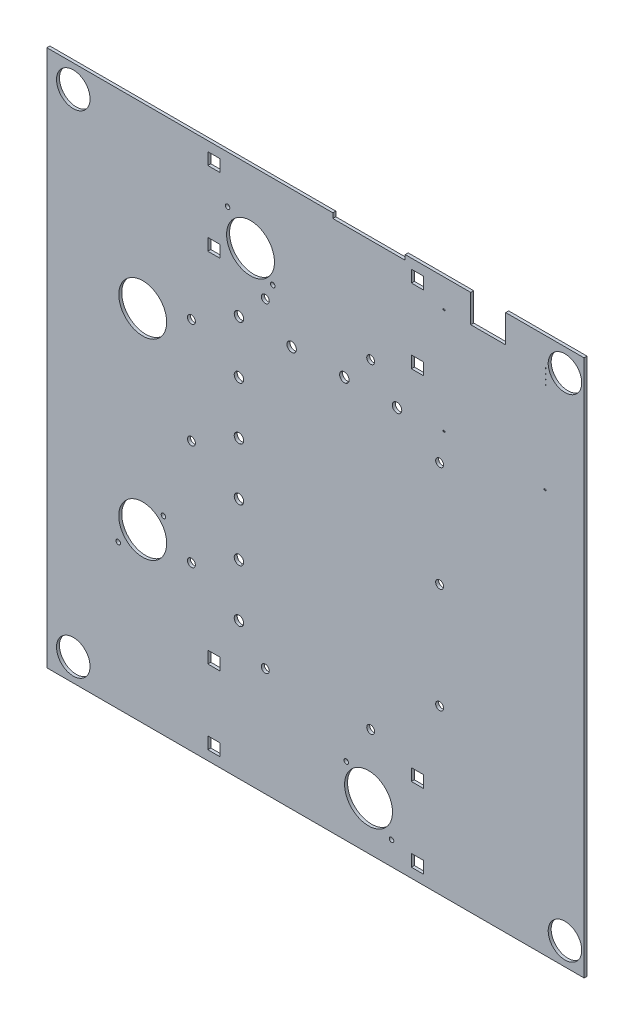
SolidWorks part; units mm, degrees
ref_plane "Front Plane" through (0, 0, 0) normal (0, 0, 1) x (1, 0, 0)
ref_plane "Top Plane" through (0, 0, 0) normal (0, 1, 0) x (1, 0, 0)
ref_plane "Right Plane" through (0, 0, 0) normal (1, 0, 0) x (0, 0, -1)
sketch "Sketch3" plane through (0, 0, 0) normal (0, 0, 1) x (1, 0, 0)
  line L0 (-165.3493, -19.4174) -> (-165.3493, -25.7674) construction
  line L1 (-165.3493, -19.4174) -> (-158.9993, -19.4174) construction
  line L2 (-216.1967, -299.1275) -> (-216.1967, -226.5584) construction
  line L3 (-133.8855, -14.3374) -> (-115.3437, -14.3374)
  line L4 (-133.8855, -14.3374) -> (-133.8855, -29.1775)
  line L5 (-133.8855, -29.1775) -> (-115.3437, -29.1775)
  line L6 (-115.3437, -14.3374) -> (-115.3437, -29.1775)
  line L7 (-168.6239, -14.3374) -> (-206.9898, -14.3374)
  line L8 (-73.7823, -14.3374) -> (-358.611, -14.3374)
  line L9 (-358.611, -14.3374) -> (-358.611, -299.1275)
  line L10 (-358.611, -299.1275) -> (-73.7823, -299.1275)
  line L11 (-73.7823, -299.1275) -> (-73.7823, -14.3374)
  line L14 (-168.6239, -14.3374) -> (-168.6239, -16.9636)
  line L15 (-168.6239, -16.9636) -> (-206.9898, -16.9636)
  line L18 (-151.6188, -156.7325) -> (-151.6188, -154.9678)
  line L19 (-216.1967, -86.8605) -> (-216.1967, -14.3374) construction
  line L20 (-158.9993, -19.4174) -> (-158.9993, -25.7674) construction
  line L21 (-165.3493, -25.7674) -> (-158.9993, -25.7674) construction
  line L22 (-165.3493, -19.4174) -> (-165.3493, -25.7674)
  line L23 (-165.3493, -19.4174) -> (-158.9993, -19.4174)
  line L24 (-158.9993, -19.4174) -> (-158.9993, -25.7674)
  line L25 (-165.3493, -25.7674) -> (-158.9993, -25.7674)
  line L27 (-165.3493, -294.0475) -> (-165.3493, -287.6975) construction
  line L28 (-165.3493, -287.6975) -> (-158.9993, -287.6975) construction
  line L29 (-158.9993, -287.6975) -> (-158.9993, -294.0475) construction
  line L30 (-158.9993, -294.0475) -> (-165.3493, -294.0475) construction
  line L31 (-158.9993, -65.1374) -> (-158.9993, -58.7874)
  line L32 (-165.3493, -65.1374) -> (-158.9993, -65.1374)
  line L33 (-165.3493, -58.7874) -> (-165.3493, -65.1374)
  line L34 (-158.9993, -58.7874) -> (-165.3493, -58.7874)
  line L35 (-158.9993, -65.1374) -> (-158.9993, -58.7874)
  line L36 (-165.3493, -65.1374) -> (-158.9993, -65.1374)
  line L37 (-165.3493, -58.7874) -> (-165.3493, -65.1374)
  line L38 (-158.9993, -58.7874) -> (-165.3493, -58.7874)
  line L39 (-266.9493, -65.1374) -> (-266.9493, -58.7874)
  line L40 (-273.2993, -65.1374) -> (-266.9493, -65.1374)
  line L41 (-273.2993, -58.7874) -> (-273.2993, -65.1374)
  line L42 (-266.9493, -58.7874) -> (-273.2993, -58.7874)
  line L43 (-266.9493, -65.1374) -> (-266.9493, -58.7874)
  line L44 (-273.2993, -65.1374) -> (-266.9493, -65.1374)
  line L45 (-273.2993, -58.7874) -> (-273.2993, -65.1374)
  line L46 (-266.9493, -58.7874) -> (-273.2993, -58.7874)
  line L47 (-266.9493, -25.7674) -> (-266.9493, -19.4174)
  line L48 (-273.2993, -25.7674) -> (-266.9493, -25.7674)
  line L49 (-273.2993, -19.4174) -> (-273.2993, -25.7674)
  line L50 (-266.9493, -19.4174) -> (-273.2993, -19.4174)
  line L51 (-266.9493, -25.7674) -> (-266.9493, -19.4174)
  line L52 (-273.2993, -25.7674) -> (-266.9493, -25.7674)
  line L53 (-273.2993, -19.4174) -> (-273.2993, -25.7674)
  line L54 (-266.9493, -19.4174) -> (-273.2993, -19.4174)
  line L55 (-165.3493, -254.6775) -> (-165.3493, -248.3275) construction
  line L56 (-165.3493, -248.3275) -> (-158.9993, -248.3275) construction
  line L57 (-158.9993, -248.3275) -> (-158.9993, -254.6775) construction
  line L58 (-158.9993, -254.6775) -> (-165.3493, -254.6775) construction
  line L59 (-273.2993, -294.0475) -> (-273.2993, -287.6975) construction
  line L60 (-273.2993, -287.6975) -> (-266.9493, -287.6975) construction
  line L61 (-266.9493, -287.6975) -> (-266.9493, -294.0475) construction
  line L62 (-266.9493, -294.0475) -> (-273.2993, -294.0475) construction
  line L63 (-273.2993, -254.6775) -> (-273.2993, -248.3275) construction
  line L64 (-273.2993, -248.3275) -> (-266.9493, -248.3275) construction
  line L65 (-266.9493, -248.3275) -> (-266.9493, -254.6775) construction
  line L66 (-266.9493, -254.6775) -> (-273.2993, -254.6775) construction
  line L67 (-165.3493, -294.0475) -> (-165.3493, -287.6975)
  line L68 (-165.3493, -287.6975) -> (-158.9993, -287.6975)
  line L69 (-158.9993, -287.6975) -> (-158.9993, -294.0475)
  line L70 (-158.9993, -294.0475) -> (-165.3493, -294.0475)
  line L71 (-165.3493, -254.6775) -> (-165.3493, -248.3275)
  line L72 (-165.3493, -248.3275) -> (-158.9993, -248.3275)
  line L73 (-158.9993, -248.3275) -> (-158.9993, -254.6775)
  line L74 (-158.9993, -254.6775) -> (-165.3493, -254.6775)
  line L75 (-273.2993, -294.0475) -> (-273.2993, -287.6975)
  line L76 (-273.2993, -287.6975) -> (-266.9493, -287.6975)
  line L77 (-266.9493, -287.6975) -> (-266.9493, -294.0475)
  line L78 (-266.9493, -294.0475) -> (-273.2993, -294.0475)
  line L79 (-273.2993, -254.6775) -> (-273.2993, -248.3275)
  line L80 (-273.2993, -248.3275) -> (-266.9493, -248.3275)
  line L81 (-266.9493, -248.3275) -> (-266.9493, -254.6775)
  line L82 (-266.9493, -254.6775) -> (-273.2993, -254.6775)
  line L120 (-116.6137, -27.9075) -> (-132.6155, -27.9075)
  line L121 (-132.6155, -27.9075) -> (-132.6155, -6.6988)
  line L122 (-132.6155, -6.6988) -> (-116.6137, -6.6988)
  line L123 (-116.6137, -6.6988) -> (-116.6137, -27.9075)
  line L124 (-205.7198, -6.6988) -> (-205.7198, -24.3985)
  line L125 (-205.7198, -24.3985) -> (-190.42, -24.3985)
  line L126 (-190.42, -24.3985) -> (-190.42, -6.6988)
  line L127 (-190.42, -6.6988) -> (-205.7198, -6.6988)
  line L128 (-185.1936, -6.6988) -> (-185.1936, -24.3985)
  line L129 (-185.1936, -24.3985) -> (-169.8939, -24.3985)
  line L130 (-169.8939, -24.3985) -> (-169.8939, -6.6988)
  line L131 (-169.8939, -6.6988) -> (-185.1936, -6.6988)
  line L132 (-147.4742, -29.0504) -> (-148.6172, -29.0504)
  line L133 (-148.6172, -29.0504) -> (-148.6172, -29.6854)
  line L134 (-148.6172, -29.6854) -> (-147.4742, -29.6854)
  line L135 (-147.4742, -29.6854) -> (-147.4742, -29.0504)
  line L136 (-147.4742, -84.9296) -> (-148.6172, -84.9296)
  line L137 (-148.6172, -84.9296) -> (-148.6172, -85.5646)
  line L138 (-148.6172, -85.5646) -> (-147.4742, -85.5646)
  line L139 (-147.4742, -85.5646) -> (-147.4742, -84.9296)
  line L140 (-95.024, -85.5646) -> (-93.881, -85.5646)
  line L141 (-93.881, -85.5646) -> (-93.881, -84.9296)
  line L142 (-93.881, -84.9296) -> (-95.024, -84.9296)
  line L143 (-95.024, -84.9296) -> (-95.024, -85.5646)
  line L144 (-95.024, -37.3053) -> (-93.881, -37.3053)
  line L145 (-93.881, -37.3053) -> (-93.881, -36.6703)
  line L146 (-93.881, -36.6703) -> (-95.024, -36.6703)
  line L147 (-95.024, -36.6703) -> (-95.024, -37.3053)
  line L148 (-95.024, -34.7654) -> (-93.881, -34.7654)
  line L149 (-93.881, -34.7654) -> (-93.881, -34.1304)
  line L150 (-93.881, -34.1304) -> (-95.024, -34.1304)
  line L151 (-95.024, -34.1304) -> (-95.024, -34.7654)
  line L152 (-95.024, -32.2254) -> (-93.881, -32.2254)
  line L153 (-93.881, -32.2254) -> (-93.881, -31.5904)
  line L154 (-93.881, -31.5904) -> (-95.024, -31.5904)
  line L155 (-95.024, -31.5904) -> (-95.024, -32.2254)
  line L156 (-95.024, -29.6854) -> (-93.881, -29.6854)
  line L157 (-93.881, -29.6854) -> (-93.881, -29.0504)
  line L158 (-93.881, -29.0504) -> (-95.024, -29.0504)
  line L159 (-95.024, -29.0504) -> (-95.024, -29.6854)
  line L160 (-94.135, -82.8976) -> (-94.135, -15.5887)
  line L161 (-100.4849, -9.2387) -> (-142.3943, -9.2387)
  line L162 (-148.7442, -15.5887) -> (-148.7442, -82.8976)
  line L163 (-136.0444, -95.5974) -> (-106.8348, -95.5974)
  line L184 (-215.778, -86.8605) -> (-216.1967, -86.8605)
  line L186 (-216.1967, -226.5584) -> (-215.778, -226.5584)
  line L224 (-204.4327, -15.6936) -> (-202.6623, -15.6936)
  line L225 (-204.1848, -12.9437) -> (-204.4327, -12.9437)
  line L226 (-202.6623, -12.9437) -> (-203.3848, -12.9437)
  line L227 (-191.7071, -12.9437) -> (-193.4774, -12.9437)
  line L228 (-191.955, -15.6936) -> (-191.7071, -15.6936)
  line L229 (-193.4774, -15.6936) -> (-192.755, -15.6936)
  line L230 (-171.181, -12.9437) -> (-172.9513, -12.9437)
  line L231 (-171.4288, -15.6936) -> (-171.181, -15.6936)
  line L232 (-172.9513, -15.6936) -> (-172.2288, -15.6936)
  line L233 (-183.9066, -15.6936) -> (-182.1362, -15.6936)
  line L234 (-183.6587, -12.9437) -> (-183.9066, -12.9437)
  line L235 (-182.1362, -12.9437) -> (-182.8587, -12.9437)
  line L236 (-206.9898, -14.3374) -> (-206.9898, -16.9636)
  line L237 (-358.611, -156.7325) -> (-73.7823, -156.7325) construction
  circle A3 centre (-250.661, -52.4374) radius 12.7
  circle A4 centre (-188.0823, -273.7275) radius 12.7
  circle A10 centre (-83.9173, -26.4411) radius 8.8899
  circle A11 centre (-344.6391, -26.4411) radius 8.8899
  circle A12 centre (-307.811, -210.2275) radius 12.7
  circle A13 centre (-307.811, -108.6275) radius 12.7
  arc A15 (-296.0366, -23.5764) -> (-295.6619, -23.6712) centre (-295.7929, -23.4014) ccw
  arc A20 (-294.3481, -26.589) -> (-294.5085, -26.9278) centre (-294.2166, -26.8586) ccw
  circle A21 centre (-242.8212, -71.7774) radius 2.1 construction
  circle A22 centre (-242.8212, -71.7774) radius 2.1
  circle A23 centre (-186.9412, -71.7774) radius 2.1 construction
  circle A24 centre (-186.9412, -71.7774) radius 2.1
  circle A25 centre (-150.3993, -100.7974) radius 2.1 construction
  circle A26 centre (-150.3993, -100.7974) radius 2.1
  circle A27 centre (-150.3993, -156.6774) radius 2.1 construction
  arc A29 (-332.9771, -238.3425) -> (-332.6024, -238.4374) centre (-332.7334, -238.1675) ccw
  arc A34 (-331.2886, -241.3551) -> (-331.449, -241.6939) centre (-331.1571, -241.6247) ccw
  circle A35 centre (-150.3993, -156.6774) radius 2.1
  circle A36 centre (-150.3993, -212.5574) radius 2.1 construction
  circle A37 centre (-150.3993, -212.5574) radius 2.1
  circle A38 centre (-186.9412, -241.5774) radius 2.1 construction
  circle A39 centre (-186.9412, -241.5774) radius 2.1
  circle A40 centre (-242.8212, -241.5774) radius 2.1 construction
  circle A41 centre (-242.8212, -241.5774) radius 2.1
  circle A42 centre (-282.0012, -212.5574) radius 2.1 construction
  circle A43 centre (-282.0012, -212.5574) radius 2.1
  circle A44 centre (-282.0012, -156.6774) radius 2.1 construction
  circle A45 centre (-282.0012, -156.6774) radius 2.1
  circle A46 centre (-282.0012, -100.7974) radius 2.1 construction
  circle A47 centre (-282.0012, -100.7974) radius 2.1
  circle A48 centre (-320.8045, -222.4214) radius 1.1994 construction
  circle A49 centre (-320.8045, -222.4214) radius 1.1994
  circle A50 centre (-296.8165, -198.4311) radius 1.1994 construction
  circle A51 centre (-296.8165, -198.4311) radius 1.1994
  circle A52 centre (-175.8884, -286.721) radius 1.1994 construction
  circle A53 centre (-175.8884, -286.721) radius 1.1994
  arc A54 (-296.0366, -23.5764) -> (-295.6619, -23.6712) centre (-295.7929, -23.4014) ccw
  circle A55 centre (-199.8787, -262.733) radius 1.1994 construction
  circle A56 centre (-199.8787, -262.733) radius 1.1994
  circle A57 centre (-262.8549, -39.4439) radius 1.1994 construction
  circle A58 centre (-262.8549, -39.4439) radius 1.1994
  arc A59 (-294.3481, -26.589) -> (-294.5085, -26.9278) centre (-294.2166, -26.8586) ccw
  circle A60 centre (-238.8646, -63.4319) radius 1.1994 construction
  arc A61 (-332.9771, -238.3425) -> (-332.6024, -238.4374) centre (-332.7334, -238.1675) ccw
  circle A62 centre (-238.8646, -63.4319) radius 1.1994
  arc A66 (-331.2886, -241.3551) -> (-331.449, -241.6939) centre (-331.1571, -241.6247) ccw
  arc A68 (-81.1216, -256.7776) -> (-81.2164, -257.1523) centre (-80.9465, -257.0213) ccw
  arc A73 (-84.1341, -258.4661) -> (-84.4729, -258.3057) centre (-84.4038, -258.5976) ccw
  arc A74 (-106.8348, -95.5974) -> (-94.135, -82.8976) centre (-106.8348, -82.8976) ccw
  arc A75 (-94.135, -15.5887) -> (-100.4849, -9.2387) centre (-100.4849, -15.5887) ccw
  arc A76 (-142.3943, -9.2387) -> (-148.7442, -15.5887) centre (-142.3943, -15.5887) ccw
  arc A77 (-148.7442, -82.8976) -> (-136.0444, -95.5974) centre (-136.0444, -82.8976) ccw
  circle A79 centre (-344.6391, -287.0239) radius 8.8899
  circle A105 centre (-83.9173, -287.0239) radius 8.8899
  arc A124 (-203.3848, -13.0248) -> (-204.1848, -13.0248) centre (-203.7848, -14.3187) ccw
  arc A125 (-202.6623, -15.6936) -> (-202.6623, -12.9437) centre (-203.7848, -14.3187) ccw
  arc A126 (-204.4327, -12.9437) -> (-204.4327, -15.6936) centre (-203.7848, -14.3187) ccw
  arc A127 (-193.4774, -12.9437) -> (-193.4774, -15.6936) centre (-192.355, -14.3187) ccw
  arc A128 (-191.7071, -15.6936) -> (-191.7071, -12.9437) centre (-192.355, -14.3187) ccw
  arc A129 (-192.755, -15.6126) -> (-191.955, -15.6126) centre (-192.355, -14.3187) ccw
  arc A130 (-172.9513, -12.9437) -> (-172.9513, -15.6936) centre (-171.8288, -14.3187) ccw
  arc A131 (-171.181, -15.6936) -> (-171.181, -12.9437) centre (-171.8288, -14.3187) ccw
  arc A132 (-182.1362, -15.6936) -> (-182.1362, -12.9437) centre (-183.2587, -14.3187) ccw
  arc A133 (-183.9066, -12.9437) -> (-183.9066, -15.6936) centre (-183.2587, -14.3187) ccw
  arc A134 (-182.8587, -13.0248) -> (-183.6587, -13.0248) centre (-183.2587, -14.3187) ccw
  circle A135 centre (-181.9887, -23.2085) radius 0.23
  circle A136 centre (-180.7187, -20.6686) radius 0.23
  circle A137 centre (-178.1787, -20.6686) radius 0.23
  circle A138 centre (-175.6388, -20.6686) radius 0.23
  circle A139 centre (-176.9088, -23.2085) radius 0.23
  circle A140 centre (-174.3688, -23.2085) radius 0.23
  circle A141 centre (-173.0988, -20.6686) radius 0.23
  spline S0 degree 3 poles (-173.0628, -89.332) (-172.7853, -89.3367) (-172.38, -89.2807) (-171.8457, -89.0944) (-171.369, -88.7792) (-170.9954, -88.3966) (-170.7252, -87.9738) (-170.5413, -87.5071) (-170.4563, -87.0124) (-170.468, -86.5105) (-170.5819, -86.0212) (-170.7877, -85.5631) (-171.0825, -85.1566) (-171.4498, -84.8146) (-171.879, -84.5546) (-172.3499, -84.382) (-172.847, -84.3088) (-173.3494, -84.3327) (-173.8366, -84.4589) (-174.2897, -84.6762) (-174.6885, -84.981) (-175.0212, -85.3565) (-175.2704, -85.7919) (-175.4312, -86.2669) (-175.492, -86.7649) (-175.456, -87.2652) (-175.3187, -87.7482) (-175.0911, -88.1957) (-174.7769, -88.5877) (-174.3932, -88.9116) (-173.9523, -89.1509) (-173.5614, -89.2712) (-173.2532, -89.3211) (-173.0628, -89.332) (-172.7853, -89.3367) (-172.38, -89.2807) knots -0.036354 -0.02215 -0.008468 0 0.030815 0.06902 0.107055 0.13877 0.170453 0.202182 0.233878 0.265639 0.297366 0.329129 0.360857 0.392587 0.424284 0.456 0.487682 0.519541 0.551366 0.583108 0.614815 0.646536 0.67822 0.709939 0.741619 0.773352 0.805047 0.836812 0.868541 0.900301 0.932026 0.963646 0.97785 0.991532 1 1.030815 1.06902 1.107055 only from (-172.9024, -89.3332) to (-172.9024, -89.3332) construction
  spline S1 degree 3 poles (-173.0628, -89.332) (-172.7853, -89.3367) (-172.38, -89.2807) (-171.8457, -89.0944) (-171.369, -88.7792) (-170.9954, -88.3966) (-170.7252, -87.9738) (-170.5413, -87.5071) (-170.4563, -87.0124) (-170.468, -86.5105) (-170.5819, -86.0212) (-170.7877, -85.5631) (-171.0825, -85.1566) (-171.4498, -84.8146) (-171.879, -84.5546) (-172.3499, -84.382) (-172.847, -84.3088) (-173.3494, -84.3327) (-173.8366, -84.4589) (-174.2897, -84.6762) (-174.6885, -84.981) (-175.0212, -85.3565) (-175.2704, -85.7919) (-175.4312, -86.2669) (-175.492, -86.7649) (-175.456, -87.2652) (-175.3187, -87.7482) (-175.0911, -88.1957) (-174.7769, -88.5877) (-174.3932, -88.9116) (-173.9523, -89.1509) (-173.5614, -89.2712) (-173.2532, -89.3211) (-173.0628, -89.332) (-172.7853, -89.3367) (-172.38, -89.2807) knots -0.036354 -0.02215 -0.008468 0 0.030815 0.06902 0.107055 0.13877 0.170453 0.202182 0.233878 0.265639 0.297366 0.329129 0.360857 0.392587 0.424284 0.456 0.487682 0.519541 0.551366 0.583108 0.614815 0.646536 0.67822 0.709939 0.741619 0.773352 0.805047 0.836812 0.868541 0.900301 0.932026 0.963646 0.97785 0.991532 1 1.030815 1.06902 1.107055 only from (-172.9024, -89.3332) to (-172.9024, -89.3332)
  spline S2 degree 3 poles (-200.8196, -84.3229) (-201.0971, -84.3182) (-201.5024, -84.3742) (-202.0367, -84.5605) (-202.5133, -84.8757) (-202.8869, -85.2583) (-203.1572, -85.681) (-203.341, -86.1477) (-203.4261, -86.6425) (-203.4143, -87.1444) (-203.3005, -87.6337) (-203.0947, -88.0918) (-202.7998, -88.4983) (-202.4325, -88.8403) (-202.0033, -89.1003) (-201.5324, -89.2729) (-201.0354, -89.3461) (-200.533, -89.3222) (-200.0457, -89.196) (-199.5927, -88.9787) (-199.1938, -88.6739) (-198.8612, -88.2984) (-198.612, -87.863) (-198.4511, -87.388) (-198.3903, -86.89) (-198.4263, -86.3896) (-198.5636, -85.9067) (-198.7912, -85.4592) (-199.1055, -85.0672) (-199.4891, -84.7433) (-199.9301, -84.504) (-200.321, -84.3837) (-200.6292, -84.3338) (-200.8196, -84.3229) (-201.0971, -84.3182) (-201.5024, -84.3742) knots -0.036354 -0.02215 -0.008468 0 0.030815 0.06902 0.107055 0.13877 0.170453 0.202182 0.233878 0.265639 0.297366 0.329129 0.360857 0.392587 0.424284 0.456 0.487682 0.519541 0.551366 0.583108 0.614815 0.646536 0.67822 0.709939 0.741619 0.773352 0.805047 0.836812 0.868541 0.900301 0.932026 0.963646 0.97785 0.991532 1 1.030815 1.06902 1.107055 only from (-200.98, -84.3216) to (-200.98, -84.3216) construction
  spline S3 degree 3 poles (-200.8196, -84.3229) (-201.0971, -84.3182) (-201.5024, -84.3742) (-202.0367, -84.5605) (-202.5133, -84.8757) (-202.8869, -85.2583) (-203.1572, -85.681) (-203.341, -86.1477) (-203.4261, -86.6425) (-203.4143, -87.1444) (-203.3005, -87.6337) (-203.0947, -88.0918) (-202.7998, -88.4983) (-202.4325, -88.8403) (-202.0033, -89.1003) (-201.5324, -89.2729) (-201.0354, -89.3461) (-200.533, -89.3222) (-200.0457, -89.196) (-199.5927, -88.9787) (-199.1938, -88.6739) (-198.8612, -88.2984) (-198.612, -87.863) (-198.4511, -87.388) (-198.3903, -86.89) (-198.4263, -86.3896) (-198.5636, -85.9067) (-198.7912, -85.4592) (-199.1055, -85.0672) (-199.4891, -84.7433) (-199.9301, -84.504) (-200.321, -84.3837) (-200.6292, -84.3338) (-200.8196, -84.3229) (-201.0971, -84.3182) (-201.5024, -84.3742) knots -0.036354 -0.02215 -0.008468 0 0.030815 0.06902 0.107055 0.13877 0.170453 0.202182 0.233878 0.265639 0.297366 0.329129 0.360857 0.392587 0.424284 0.456 0.487682 0.519541 0.551366 0.583108 0.614815 0.646536 0.67822 0.709939 0.741619 0.773352 0.805047 0.836812 0.868541 0.900301 0.932026 0.963646 0.97785 0.991532 1 1.030815 1.06902 1.107055 only from (-200.98, -84.3216) to (-200.98, -84.3216)
  spline S4 degree 3 poles (-256.6996, -224.0229) (-256.9771, -224.0182) (-257.3824, -224.0742) (-257.9167, -224.2605) (-258.3933, -224.5757) (-258.7669, -224.9583) (-259.0372, -225.381) (-259.221, -225.8477) (-259.3061, -226.3425) (-259.2943, -226.8444) (-259.1805, -227.3337) (-258.9747, -227.7918) (-258.6798, -228.1983) (-258.3125, -228.5403) (-257.8833, -228.8003) (-257.4124, -228.9729) (-256.9154, -229.0461) (-256.413, -229.0222) (-255.9257, -228.896) (-255.4727, -228.6787) (-255.0738, -228.3739) (-254.7412, -227.9984) (-254.492, -227.563) (-254.3311, -227.088) (-254.2703, -226.59) (-254.3063, -226.0896) (-254.4436, -225.6067) (-254.6712, -225.1592) (-254.9855, -224.7672) (-255.3691, -224.4433) (-255.8101, -224.204) (-256.201, -224.0837) (-256.5092, -224.0338) (-256.6996, -224.0229) (-256.9771, -224.0182) (-257.3824, -224.0742) knots -0.036354 -0.02215 -0.008468 0 0.030815 0.06902 0.107055 0.13877 0.170453 0.202182 0.233878 0.265639 0.297366 0.329129 0.360857 0.392587 0.424284 0.456 0.487682 0.519541 0.551366 0.583108 0.614815 0.646536 0.67822 0.709939 0.741619 0.773352 0.805047 0.836812 0.868541 0.900301 0.932026 0.963646 0.97785 0.991532 1 1.030815 1.06902 1.107055 only from (-256.86, -224.0216) to (-256.86, -224.0216) construction
  spline S5 degree 3 poles (-256.6996, -224.0229) (-256.9771, -224.0182) (-257.3824, -224.0742) (-257.9167, -224.2605) (-258.3933, -224.5757) (-258.7669, -224.9583) (-259.0372, -225.381) (-259.221, -225.8477) (-259.3061, -226.3425) (-259.2943, -226.8444) (-259.1805, -227.3337) (-258.9747, -227.7918) (-258.6798, -228.1983) (-258.3125, -228.5403) (-257.8833, -228.8003) (-257.4124, -228.9729) (-256.9154, -229.0461) (-256.413, -229.0222) (-255.9257, -228.896) (-255.4727, -228.6787) (-255.0738, -228.3739) (-254.7412, -227.9984) (-254.492, -227.563) (-254.3311, -227.088) (-254.2703, -226.59) (-254.3063, -226.0896) (-254.4436, -225.6067) (-254.6712, -225.1592) (-254.9855, -224.7672) (-255.3691, -224.4433) (-255.8101, -224.204) (-256.201, -224.0837) (-256.5092, -224.0338) (-256.6996, -224.0229) (-256.9771, -224.0182) (-257.3824, -224.0742) knots -0.036354 -0.02215 -0.008468 0 0.030815 0.06902 0.107055 0.13877 0.170453 0.202182 0.233878 0.265639 0.297366 0.329129 0.360857 0.392587 0.424284 0.456 0.487682 0.519541 0.551366 0.583108 0.614815 0.646536 0.67822 0.709939 0.741619 0.773352 0.805047 0.836812 0.868541 0.900301 0.932026 0.963646 0.97785 0.991532 1 1.030815 1.06902 1.107055 only from (-256.86, -224.0216) to (-256.86, -224.0216)
  spline S6 degree 3 poles (-256.6996, -196.0829) (-256.9771, -196.0782) (-257.3824, -196.1342) (-257.9167, -196.3205) (-258.3933, -196.6357) (-258.7669, -197.0183) (-259.0372, -197.441) (-259.221, -197.9077) (-259.3061, -198.4025) (-259.2943, -198.9044) (-259.1805, -199.3937) (-258.9747, -199.8518) (-258.6798, -200.2583) (-258.3125, -200.6003) (-257.8833, -200.8603) (-257.4124, -201.0329) (-256.9154, -201.1061) (-256.413, -201.0822) (-255.9257, -200.956) (-255.4727, -200.7387) (-255.0738, -200.4339) (-254.7412, -200.0584) (-254.492, -199.623) (-254.3311, -199.148) (-254.2703, -198.65) (-254.3063, -198.1496) (-254.4436, -197.6667) (-254.6712, -197.2192) (-254.9855, -196.8272) (-255.3691, -196.5033) (-255.8101, -196.264) (-256.201, -196.1437) (-256.5092, -196.0938) (-256.6996, -196.0829) (-256.9771, -196.0782) (-257.3824, -196.1342) knots -0.036354 -0.02215 -0.008468 0 0.030815 0.06902 0.107055 0.13877 0.170453 0.202182 0.233878 0.265639 0.297366 0.329129 0.360857 0.392587 0.424284 0.456 0.487682 0.519541 0.551366 0.583108 0.614815 0.646536 0.67822 0.709939 0.741619 0.773352 0.805047 0.836812 0.868541 0.900301 0.932026 0.963646 0.97785 0.991532 1 1.030815 1.06902 1.107055 only from (-256.86, -196.0816) to (-256.86, -196.0816) construction
  spline S7 degree 3 poles (-256.6996, -196.0829) (-256.9771, -196.0782) (-257.3824, -196.1342) (-257.9167, -196.3205) (-258.3933, -196.6357) (-258.7669, -197.0183) (-259.0372, -197.441) (-259.221, -197.9077) (-259.3061, -198.4025) (-259.2943, -198.9044) (-259.1805, -199.3937) (-258.9747, -199.8518) (-258.6798, -200.2583) (-258.3125, -200.6003) (-257.8833, -200.8603) (-257.4124, -201.0329) (-256.9154, -201.1061) (-256.413, -201.0822) (-255.9257, -200.956) (-255.4727, -200.7387) (-255.0738, -200.4339) (-254.7412, -200.0584) (-254.492, -199.623) (-254.3311, -199.148) (-254.2703, -198.65) (-254.3063, -198.1496) (-254.4436, -197.6667) (-254.6712, -197.2192) (-254.9855, -196.8272) (-255.3691, -196.5033) (-255.8101, -196.264) (-256.201, -196.1437) (-256.5092, -196.0938) (-256.6996, -196.0829) (-256.9771, -196.0782) (-257.3824, -196.1342) knots -0.036354 -0.02215 -0.008468 0 0.030815 0.06902 0.107055 0.13877 0.170453 0.202182 0.233878 0.265639 0.297366 0.329129 0.360857 0.392587 0.424284 0.456 0.487682 0.519541 0.551366 0.583108 0.614815 0.646536 0.67822 0.709939 0.741619 0.773352 0.805047 0.836812 0.868541 0.900301 0.932026 0.963646 0.97785 0.991532 1 1.030815 1.06902 1.107055 only from (-256.86, -196.0816) to (-256.86, -196.0816)
  spline S8 degree 3 poles (-256.6996, -168.1429) (-256.9771, -168.1382) (-257.3824, -168.1942) (-257.9167, -168.3805) (-258.3933, -168.6957) (-258.7669, -169.0783) (-259.0372, -169.501) (-259.221, -169.9677) (-259.3061, -170.4625) (-259.2943, -170.9644) (-259.1805, -171.4537) (-258.9747, -171.9118) (-258.6798, -172.3183) (-258.3125, -172.6603) (-257.8833, -172.9203) (-257.4124, -173.0929) (-256.9154, -173.1661) (-256.413, -173.1422) (-255.9257, -173.016) (-255.4727, -172.7987) (-255.0738, -172.4939) (-254.7412, -172.1184) (-254.492, -171.683) (-254.3311, -171.208) (-254.2703, -170.71) (-254.3063, -170.2096) (-254.4436, -169.7267) (-254.6712, -169.2792) (-254.9855, -168.8872) (-255.3691, -168.5633) (-255.8101, -168.324) (-256.201, -168.2037) (-256.5092, -168.1538) (-256.6996, -168.1429) (-256.9771, -168.1382) (-257.3824, -168.1942) knots -0.036354 -0.02215 -0.008468 0 0.030815 0.06902 0.107055 0.13877 0.170453 0.202182 0.233878 0.265639 0.297366 0.329129 0.360857 0.392587 0.424284 0.456 0.487682 0.519541 0.551366 0.583108 0.614815 0.646536 0.67822 0.709939 0.741619 0.773352 0.805047 0.836812 0.868541 0.900301 0.932026 0.963646 0.97785 0.991532 1 1.030815 1.06902 1.107055 only from (-256.86, -168.1416) to (-256.86, -168.1416) construction
  spline S9 degree 3 poles (-204.1848, -12.9437) (-204.1852, -12.9708) (-204.1852, -12.9978) (-204.1848, -13.0248) knots 0 0 0 0 1 1 1 1
  spline S10 degree 3 poles (-203.3848, -13.0248) (-203.3844, -12.9978) (-203.3844, -12.9708) (-203.3848, -12.9437) knots 0 0 0 0 1 1 1 1
  spline S11 degree 3 poles (-191.955, -15.6936) (-191.9545, -15.6666) (-191.9545, -15.6395) (-191.955, -15.6126) knots 0 0 0 0 1 1 1 1
  spline S12 degree 3 poles (-192.755, -15.6126) (-192.7554, -15.6395) (-192.7554, -15.6666) (-192.755, -15.6936) knots 0 0 0 0 1 1 1 1
  spline S13 degree 3 poles (-171.4288, -15.6936) (-171.4284, -15.6666) (-171.4284, -15.6395) (-171.4288, -15.6126) knots 0 0 0 0 1 1 1 1
  spline S14 degree 3 poles (-172.2288, -15.6126) (-172.2293, -15.6395) (-172.2293, -15.6666) (-172.2288, -15.6936) knots 0 0 0 0 1 1 1 1
  spline S15 degree 3 poles (-183.6587, -12.9437) (-183.6591, -12.9708) (-183.6591, -12.9978) (-183.6587, -13.0248) knots 0 0 0 0 1 1 1 1
  spline S16 degree 3 poles (-182.8587, -13.0248) (-182.8582, -12.9978) (-182.8582, -12.9708) (-182.8587, -12.9437) knots 0 0 0 0 1 1 1 1
  spline S17 degree 3 poles (-179.6787, -23.2085) (-179.6787, -23.6685) (-179.2187, -23.6685) (-179.2187, -23.2085) (-179.2187, -22.7485) (-179.6787, -22.7485) (-179.6787, -23.2085) (-179.6787, -23.6685) (-179.2187, -23.6685) knots -0.5 0 0 0 0.5 0.5 0.5 1 1 1 1.5 1.5 1.5 weights 1 0.333333 0.333333 1 0.333333 0.333333 1 0.333333 0.333333 only from (-179.6787, -23.2085) to (-179.6787, -23.2085)
  spline S18 degree 3 poles (-256.6996, -168.1429) (-256.9771, -168.1382) (-257.3824, -168.1942) (-257.9167, -168.3805) (-258.3933, -168.6957) (-258.7669, -169.0783) (-259.0372, -169.501) (-259.221, -169.9677) (-259.3061, -170.4625) (-259.2943, -170.9644) (-259.1805, -171.4537) (-258.9747, -171.9118) (-258.6798, -172.3183) (-258.3125, -172.6603) (-257.8833, -172.9203) (-257.4124, -173.0929) (-256.9154, -173.1661) (-256.413, -173.1422) (-255.9257, -173.016) (-255.4727, -172.7987) (-255.0738, -172.4939) (-254.7412, -172.1184) (-254.492, -171.683) (-254.3311, -171.208) (-254.2703, -170.71) (-254.3063, -170.2096) (-254.4436, -169.7267) (-254.6712, -169.2792) (-254.9855, -168.8872) (-255.3691, -168.5633) (-255.8101, -168.324) (-256.201, -168.2037) (-256.5092, -168.1538) (-256.6996, -168.1429) (-256.9771, -168.1382) (-257.3824, -168.1942) knots -0.036354 -0.02215 -0.008468 0 0.030815 0.06902 0.107055 0.13877 0.170453 0.202182 0.233878 0.265639 0.297366 0.329129 0.360857 0.392587 0.424284 0.456 0.487682 0.519541 0.551366 0.583108 0.614815 0.646536 0.67822 0.709939 0.741619 0.773352 0.805047 0.836812 0.868541 0.900301 0.932026 0.963646 0.97785 0.991532 1 1.030815 1.06902 1.107055 only from (-256.86, -168.1416) to (-256.86, -168.1416)
  spline S19 degree 3 poles (-256.6996, -140.2029) (-256.9771, -140.1982) (-257.3824, -140.2542) (-257.9167, -140.4405) (-258.3933, -140.7557) (-258.7669, -141.1383) (-259.0372, -141.561) (-259.221, -142.0277) (-259.3061, -142.5225) (-259.2943, -143.0244) (-259.1805, -143.5137) (-258.9747, -143.9718) (-258.6798, -144.3783) (-258.3125, -144.7203) (-257.8833, -144.9803) (-257.4124, -145.1529) (-256.9154, -145.2261) (-256.413, -145.2022) (-255.9257, -145.076) (-255.4727, -144.8587) (-255.0738, -144.5539) (-254.7412, -144.1784) (-254.492, -143.743) (-254.3311, -143.268) (-254.2703, -142.77) (-254.3063, -142.2696) (-254.4436, -141.7867) (-254.6712, -141.3392) (-254.9855, -140.9472) (-255.3691, -140.6233) (-255.8101, -140.384) (-256.201, -140.2637) (-256.5092, -140.2138) (-256.6996, -140.2029) (-256.9771, -140.1982) (-257.3824, -140.2542) knots -0.036354 -0.02215 -0.008468 0 0.030815 0.06902 0.107055 0.13877 0.170453 0.202182 0.233878 0.265639 0.297366 0.329129 0.360857 0.392587 0.424284 0.456 0.487682 0.519541 0.551366 0.583108 0.614815 0.646536 0.67822 0.709939 0.741619 0.773352 0.805047 0.836812 0.868541 0.900301 0.932026 0.963646 0.97785 0.991532 1 1.030815 1.06902 1.107055 only from (-256.86, -140.2016) to (-256.86, -140.2016) construction
  spline S20 degree 3 poles (-256.6996, -140.2029) (-256.9771, -140.1982) (-257.3824, -140.2542) (-257.9167, -140.4405) (-258.3933, -140.7557) (-258.7669, -141.1383) (-259.0372, -141.561) (-259.221, -142.0277) (-259.3061, -142.5225) (-259.2943, -143.0244) (-259.1805, -143.5137) (-258.9747, -143.9718) (-258.6798, -144.3783) (-258.3125, -144.7203) (-257.8833, -144.9803) (-257.4124, -145.1529) (-256.9154, -145.2261) (-256.413, -145.2022) (-255.9257, -145.076) (-255.4727, -144.8587) (-255.0738, -144.5539) (-254.7412, -144.1784) (-254.492, -143.743) (-254.3311, -143.268) (-254.2703, -142.77) (-254.3063, -142.2696) (-254.4436, -141.7867) (-254.6712, -141.3392) (-254.9855, -140.9472) (-255.3691, -140.6233) (-255.8101, -140.384) (-256.201, -140.2637) (-256.5092, -140.2138) (-256.6996, -140.2029) (-256.9771, -140.1982) (-257.3824, -140.2542) knots -0.036354 -0.02215 -0.008468 0 0.030815 0.06902 0.107055 0.13877 0.170453 0.202182 0.233878 0.265639 0.297366 0.329129 0.360857 0.392587 0.424284 0.456 0.487682 0.519541 0.551366 0.583108 0.614815 0.646536 0.67822 0.709939 0.741619 0.773352 0.805047 0.836812 0.868541 0.900301 0.932026 0.963646 0.97785 0.991532 1 1.030815 1.06902 1.107055 only from (-256.86, -140.2016) to (-256.86, -140.2016)
  spline S21 degree 3 poles (-256.6996, -112.2629) (-256.9771, -112.2582) (-257.3824, -112.3142) (-257.9167, -112.5005) (-258.3933, -112.8157) (-258.7669, -113.1983) (-259.0372, -113.621) (-259.221, -114.0877) (-259.3061, -114.5825) (-259.2943, -115.0844) (-259.1805, -115.5737) (-258.9747, -116.0318) (-258.6798, -116.4383) (-258.3125, -116.7803) (-257.8833, -117.0403) (-257.4124, -117.2129) (-256.9154, -117.2861) (-256.413, -117.2622) (-255.9257, -117.136) (-255.4727, -116.9187) (-255.0738, -116.6139) (-254.7412, -116.2384) (-254.492, -115.803) (-254.3311, -115.328) (-254.2703, -114.83) (-254.3063, -114.3296) (-254.4436, -113.8467) (-254.6712, -113.3992) (-254.9855, -113.0072) (-255.3691, -112.6833) (-255.8101, -112.444) (-256.201, -112.3237) (-256.5092, -112.2738) (-256.6996, -112.2629) (-256.9771, -112.2582) (-257.3824, -112.3142) knots -0.036354 -0.02215 -0.008468 0 0.030815 0.06902 0.107055 0.13877 0.170453 0.202182 0.233878 0.265639 0.297366 0.329129 0.360857 0.392587 0.424284 0.456 0.487682 0.519541 0.551366 0.583108 0.614815 0.646536 0.67822 0.709939 0.741619 0.773352 0.805047 0.836812 0.868541 0.900301 0.932026 0.963646 0.97785 0.991532 1 1.030815 1.06902 1.107055 only from (-256.86, -112.2616) to (-256.86, -112.2616) construction
  spline S22 degree 3 poles (-256.6996, -112.2629) (-256.9771, -112.2582) (-257.3824, -112.3142) (-257.9167, -112.5005) (-258.3933, -112.8157) (-258.7669, -113.1983) (-259.0372, -113.621) (-259.221, -114.0877) (-259.3061, -114.5825) (-259.2943, -115.0844) (-259.1805, -115.5737) (-258.9747, -116.0318) (-258.6798, -116.4383) (-258.3125, -116.7803) (-257.8833, -117.0403) (-257.4124, -117.2129) (-256.9154, -117.2861) (-256.413, -117.2622) (-255.9257, -117.136) (-255.4727, -116.9187) (-255.0738, -116.6139) (-254.7412, -116.2384) (-254.492, -115.803) (-254.3311, -115.328) (-254.2703, -114.83) (-254.3063, -114.3296) (-254.4436, -113.8467) (-254.6712, -113.3992) (-254.9855, -113.0072) (-255.3691, -112.6833) (-255.8101, -112.444) (-256.201, -112.3237) (-256.5092, -112.2738) (-256.6996, -112.2629) (-256.9771, -112.2582) (-257.3824, -112.3142) knots -0.036354 -0.02215 -0.008468 0 0.030815 0.06902 0.107055 0.13877 0.170453 0.202182 0.233878 0.265639 0.297366 0.329129 0.360857 0.392587 0.424284 0.456 0.487682 0.519541 0.551366 0.583108 0.614815 0.646536 0.67822 0.709939 0.741619 0.773352 0.805047 0.836812 0.868541 0.900301 0.932026 0.963646 0.97785 0.991532 1 1.030815 1.06902 1.107055 only from (-256.86, -112.2616) to (-256.86, -112.2616)
  spline S23 degree 3 poles (-256.6996, -84.3229) (-256.9771, -84.3182) (-257.3824, -84.3742) (-257.9167, -84.5605) (-258.3933, -84.8757) (-258.7669, -85.2583) (-259.0372, -85.681) (-259.221, -86.1477) (-259.3061, -86.6425) (-259.2943, -87.1444) (-259.1805, -87.6337) (-258.9747, -88.0918) (-258.6798, -88.4983) (-258.3125, -88.8403) (-257.8833, -89.1003) (-257.4124, -89.2729) (-256.9154, -89.3461) (-256.413, -89.3222) (-255.9257, -89.196) (-255.4727, -88.9787) (-255.0738, -88.6739) (-254.7412, -88.2984) (-254.492, -87.863) (-254.3311, -87.388) (-254.2703, -86.89) (-254.3063, -86.3896) (-254.4436, -85.9067) (-254.6712, -85.4592) (-254.9855, -85.0672) (-255.3691, -84.7433) (-255.8101, -84.504) (-256.201, -84.3837) (-256.5092, -84.3338) (-256.6996, -84.3229) (-256.9771, -84.3182) (-257.3824, -84.3742) knots -0.036354 -0.02215 -0.008468 0 0.030815 0.06902 0.107055 0.13877 0.170453 0.202182 0.233878 0.265639 0.297366 0.329129 0.360857 0.392587 0.424284 0.456 0.487682 0.519541 0.551366 0.583108 0.614815 0.646536 0.67822 0.709939 0.741619 0.773352 0.805047 0.836812 0.868541 0.900301 0.932026 0.963646 0.97785 0.991532 1 1.030815 1.06902 1.107055 only from (-256.86, -84.3216) to (-256.86, -84.3216) construction
  spline S24 degree 3 poles (-256.6996, -84.3229) (-256.9771, -84.3182) (-257.3824, -84.3742) (-257.9167, -84.5605) (-258.3933, -84.8757) (-258.7669, -85.2583) (-259.0372, -85.681) (-259.221, -86.1477) (-259.3061, -86.6425) (-259.2943, -87.1444) (-259.1805, -87.6337) (-258.9747, -88.0918) (-258.6798, -88.4983) (-258.3125, -88.8403) (-257.8833, -89.1003) (-257.4124, -89.2729) (-256.9154, -89.3461) (-256.413, -89.3222) (-255.9257, -89.196) (-255.4727, -88.9787) (-255.0738, -88.6739) (-254.7412, -88.2984) (-254.492, -87.863) (-254.3311, -87.388) (-254.2703, -86.89) (-254.3063, -86.3896) (-254.4436, -85.9067) (-254.6712, -85.4592) (-254.9855, -85.0672) (-255.3691, -84.7433) (-255.8101, -84.504) (-256.201, -84.3837) (-256.5092, -84.3338) (-256.6996, -84.3229) (-256.9771, -84.3182) (-257.3824, -84.3742) knots -0.036354 -0.02215 -0.008468 0 0.030815 0.06902 0.107055 0.13877 0.170453 0.202182 0.233878 0.265639 0.297366 0.329129 0.360857 0.392587 0.424284 0.456 0.487682 0.519541 0.551366 0.583108 0.614815 0.646536 0.67822 0.709939 0.741619 0.773352 0.805047 0.836812 0.868541 0.900301 0.932026 0.963646 0.97785 0.991532 1 1.030815 1.06902 1.107055 only from (-256.86, -84.3216) to (-256.86, -84.3216)
  spline S25 degree 3 poles (-228.9428, -89.332) (-228.6653, -89.3367) (-228.26, -89.2807) (-227.7257, -89.0944) (-227.249, -88.7792) (-226.8754, -88.3966) (-226.6052, -87.9738) (-226.4213, -87.5071) (-226.3363, -87.0124) (-226.348, -86.5105) (-226.4619, -86.0212) (-226.6677, -85.5631) (-226.9625, -85.1566) (-227.3298, -84.8146) (-227.759, -84.5546) (-228.2299, -84.382) (-228.727, -84.3088) (-229.2294, -84.3327) (-229.7166, -84.4589) (-230.1697, -84.6762) (-230.5685, -84.981) (-230.9012, -85.3565) (-231.1504, -85.7919) (-231.3112, -86.2669) (-231.372, -86.7649) (-231.336, -87.2652) (-231.1987, -87.7482) (-230.9711, -88.1957) (-230.6569, -88.5877) (-230.2732, -88.9116) (-229.8323, -89.1509) (-229.4414, -89.2712) (-229.1332, -89.3211) (-228.9428, -89.332) (-228.6653, -89.3367) (-228.26, -89.2807) knots -0.036354 -0.02215 -0.008468 0 0.030815 0.06902 0.107055 0.13877 0.170453 0.202182 0.233878 0.265639 0.297366 0.329129 0.360857 0.392587 0.424284 0.456 0.487682 0.519541 0.551366 0.583108 0.614815 0.646536 0.67822 0.709939 0.741619 0.773352 0.805047 0.836812 0.868541 0.900301 0.932026 0.963646 0.97785 0.991532 1 1.030815 1.06902 1.107055 only from (-228.7824, -89.3332) to (-228.7824, -89.3332) construction
  spline S26 degree 3 poles (-228.9428, -89.332) (-228.6653, -89.3367) (-228.26, -89.2807) (-227.7257, -89.0944) (-227.249, -88.7792) (-226.8754, -88.3966) (-226.6052, -87.9738) (-226.4213, -87.5071) (-226.3363, -87.0124) (-226.348, -86.5105) (-226.4619, -86.0212) (-226.6677, -85.5631) (-226.9625, -85.1566) (-227.3298, -84.8146) (-227.759, -84.5546) (-228.2299, -84.382) (-228.727, -84.3088) (-229.2294, -84.3327) (-229.7166, -84.4589) (-230.1697, -84.6762) (-230.5685, -84.981) (-230.9012, -85.3565) (-231.1504, -85.7919) (-231.3112, -86.2669) (-231.372, -86.7649) (-231.336, -87.2652) (-231.1987, -87.7482) (-230.9711, -88.1957) (-230.6569, -88.5877) (-230.2732, -88.9116) (-229.8323, -89.1509) (-229.4414, -89.2712) (-229.1332, -89.3211) (-228.9428, -89.332) (-228.6653, -89.3367) (-228.26, -89.2807) knots -0.036354 -0.02215 -0.008468 0 0.030815 0.06902 0.107055 0.13877 0.170453 0.202182 0.233878 0.265639 0.297366 0.329129 0.360857 0.392587 0.424284 0.456 0.487682 0.519541 0.551366 0.583108 0.614815 0.646536 0.67822 0.709939 0.741619 0.773352 0.805047 0.836812 0.868541 0.900301 0.932026 0.963646 0.97785 0.991532 1 1.030815 1.06902 1.107055 only from (-228.7824, -89.3332) to (-228.7824, -89.3332)
  point P2 (-303.7523, -29.1184)
  dimension "D7" = 107.95
  dimension "D9" = 25.4
  dimension "D11" = 25.4
  dimension "D12" = 25.4
  dimension "D10" = 25.4
  dimension "D13" = 101.6
  dimension "D16" = 114.3
  dimension "D18" = 25.4
  dimension "D1" = 1.27
  dimension "D2" = 1.27
  dimension "D3" = 1.27
  dimension "D4" = 1.27
  dimension "D5" = 1.27
  dimension "D6" = 1.27
  dimension "D8" = 38.1
  dimension "D14" = 50.8
  dimension "D15" = 88.9
  dimension "D17" = 284.8287
  dimension "D19" = 0
  dimension "D20" = 0
  dimension "D21" = 0
extrude "Boss-Extrude1" add sketch "Sketch3" along normal blind 1.5748 contours A77 L162 A76 L8 L14 L15 L130 L129 L128 L126 L125 L124 L236 L9 L10 L11 A75 L160 L158 L157 L156 L154 L153 L152 L150 L149 L148 L146 L145 L144 A74 L142 L141 L140 L163 L138 L137 L136 A105 | L144 L160 L146 L147 | L148 L160 L150 L151 | L152 L160 L154 L155 | L156 L160 L158 L159 | L162 A77 L136 L139 L138 L163 A74 L140 L143 L142 L160 L144 L147 L146 L148 L151 L150 L152 L155 L154 L156 L159 L158 A75 L8 L6 L5 L4 A76 L135 L134 L133 L132 | L129 L130 L15 L128 S17 A141 A140 A139 A138 A137 A136 A135 | L125 L126 L15 L124 | A135 | S17 | A136 | A137 | A139 | A138 | A140 | A141
